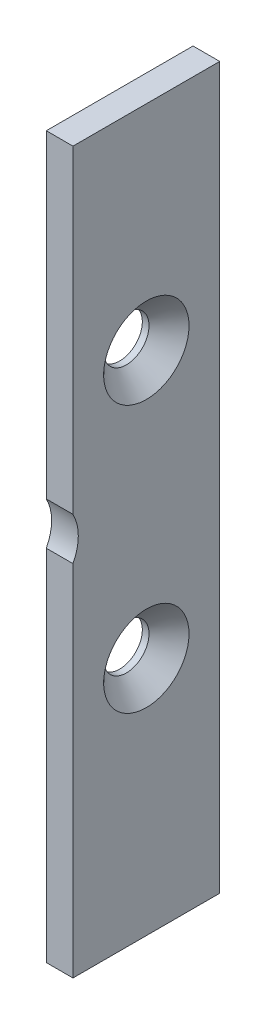
SolidWorks part; units mm, degrees
other "Preload Guide Rod End Stop"
other "Preload Guide Rod End Stop Left"
ref_plane "Front Plane" through (0, 0, 0) normal (0, 0, 1) x (1, 0, 0)
ref_plane "Top Plane" through (0, 0, 0) normal (0, 1, 0) x (1, 0, 0)
ref_plane "Right Plane" through (0, 0, 0) normal (1, 0, 0) x (0, 0, -1)
sketch3d "End stop sheet sketch datum points"
  point P0 (58.2, -54.5, -33.5)
  point P1 (68.2, -54.5, -33.5)
  point P2 (58.2, -44.5, -33.5)
ref_plane "End stop sheet sketch plane" through (0, 0, -33.5) normal (0, 0, 1) x (1, 0, 0)
sketch "End stop sheet sketch" plane through (0, 0, -33.5) normal (0, 0, 1) x (1, 0, 0)
  line L0 (58.2, -54.5) -> (60.2, -54.5)
  line L1 (60.2, -54.5) -> (60.2, -0.5)
  line L2 (60.2, -0.5) -> (58.2, -0.5)
  line L3 (58.2, -0.5) -> (58.2, -54.5)
extrude "End stop sheet" add sketch "End stop sheet sketch" along normal blind 11 separate body
sketch3d "Screw end clearance sketch datum points"
  point P0 (58.1, -29, -19.5)
  point P1 (58.1, -19, -19.5)
  point P2 (58.1, -29, -9.5)
ref_plane "Screw end clearance sketch plane" through (58.1, 0, 0) normal (1, 0, 0) x (0, 0, -1)
sketch "Screw end clearance sketch" plane through (58.1, 0, 0) normal (1, 0, 0) x (0, 0, -1)
  circle A0 centre (19.5, -29) radius 3.4
extrude "Screw end clearance" cut sketch "Screw end clearance sketch" along normal blind 2.2
sketch3d "M3 countersunk clearance 1 bore profile datum points"
  point P0 (60.2, -18.5, -28)
  point P1 (60.2, -8.5, -28)
  point P2 (60.2, -18.5, -38)
ref_plane "M3 countersunk clearance 1 bore profile plane" through (60.2, 0, 0) normal (-1, 0, 0) x (0, 0, 1)
sketch "M3 countersunk clearance 1 bore profile" plane through (60.2, 0, 0) normal (-1, 0, 0) x (0, 0, 1)
  circle A0 centre (-28, -18.5) radius 1.7
extrude "M3 countersunk clearance 1 bore" cut sketch "M3 countersunk clearance 1 bore profile" along normal blind 2.2
sketch3d "M3 countersunk clearance 1 countersink axis line"
  line L0 (70.2, -18.5, -28) -> (50.2, -18.5, -28) construction
ref_axis "M3 countersunk clearance 1 countersink axis" through (70.2, -18.5, -28) along (-1, 0, 0)
sketch3d "M3 countersunk clearance 1 countersink profile datum points"
  point P0 (60.2, -18.5, -28)
  point P1 (60.2, -8.5, -28)
  point P2 (50.2, -18.5, -28)
ref_plane "M3 countersunk clearance 1 countersink profile plane" through (0, 0, -28) normal (0, 0, 1) x (1, 0, 0)
sketch "M3 countersunk clearance 1 countersink profile" plane through (0, 0, -28) normal (0, 0, 1) x (1, 0, 0)
  line L0 (60.2, -18.5) -> (60.2, -15.3)
  line L1 (60.2, -15.3) -> (58.7, -16.8)
  line L2 (58.7, -16.8) -> (58.7, -18.5)
  line L3 (58.7, -18.5) -> (60.2, -18.5)
revolve "M3 countersunk clearance 1 countersink" cut sketch "M3 countersunk clearance 1 countersink profile" angle 360 about axis through (70.2, -18.5, -28) along (-1, 0, 0)
sketch3d "M3 countersunk clearance 2 bore profile datum points"
  point P0 (60.2, -38.5, -28)
  point P1 (60.2, -28.5, -28)
  point P2 (60.2, -38.5, -38)
ref_plane "M3 countersunk clearance 2 bore profile plane" through (60.2, 0, 0) normal (-1, 0, 0) x (0, 0, 1)
sketch "M3 countersunk clearance 2 bore profile" plane through (60.2, 0, 0) normal (-1, 0, 0) x (0, 0, 1)
  circle A0 centre (-28, -38.5) radius 1.7
extrude "M3 countersunk clearance 2 bore" cut sketch "M3 countersunk clearance 2 bore profile" along normal blind 2.2
sketch3d "M3 countersunk clearance 2 countersink axis line"
  line L0 (70.2, -38.5, -28) -> (50.2, -38.5, -28) construction
ref_axis "M3 countersunk clearance 2 countersink axis" through (70.2, -38.5, -28) along (-1, 0, 0)
sketch3d "M3 countersunk clearance 2 countersink profile datum points"
  point P0 (60.2, -38.5, -28)
  point P1 (60.2, -28.5, -28)
  point P2 (50.2, -38.5, -28)
ref_plane "M3 countersunk clearance 2 countersink profile plane" through (0, 0, -28) normal (0, 0, 1) x (1, 0, 0)
sketch "M3 countersunk clearance 2 countersink profile" plane through (0, 0, -28) normal (0, 0, 1) x (1, 0, 0)
  line L0 (60.2, -38.5) -> (60.2, -35.3)
  line L1 (60.2, -35.3) -> (58.7, -36.8)
  line L2 (58.7, -36.8) -> (58.7, -38.5)
  line L3 (58.7, -38.5) -> (60.2, -38.5)
revolve "M3 countersunk clearance 2 countersink" cut sketch "M3 countersunk clearance 2 countersink profile" angle 360 about axis through (70.2, -38.5, -28) along (-1, 0, 0)
sketch3d "Mirror1 profile datum points"
  point P0 (0, 0, 0)
  point P1 (10, 0, 0)
  point P2 (0, 0, 10)
ref_plane "Mirror1 profile plane" through (0, 0, 0) normal (0, -1, 0) x (-1, 0, 0)
mirror "Mirror1" about plane through (0, 0, 0) normal (0, -1, 0) of bodies 106
delete or keep bodies "Remove1" type delete bodies bodies 106
